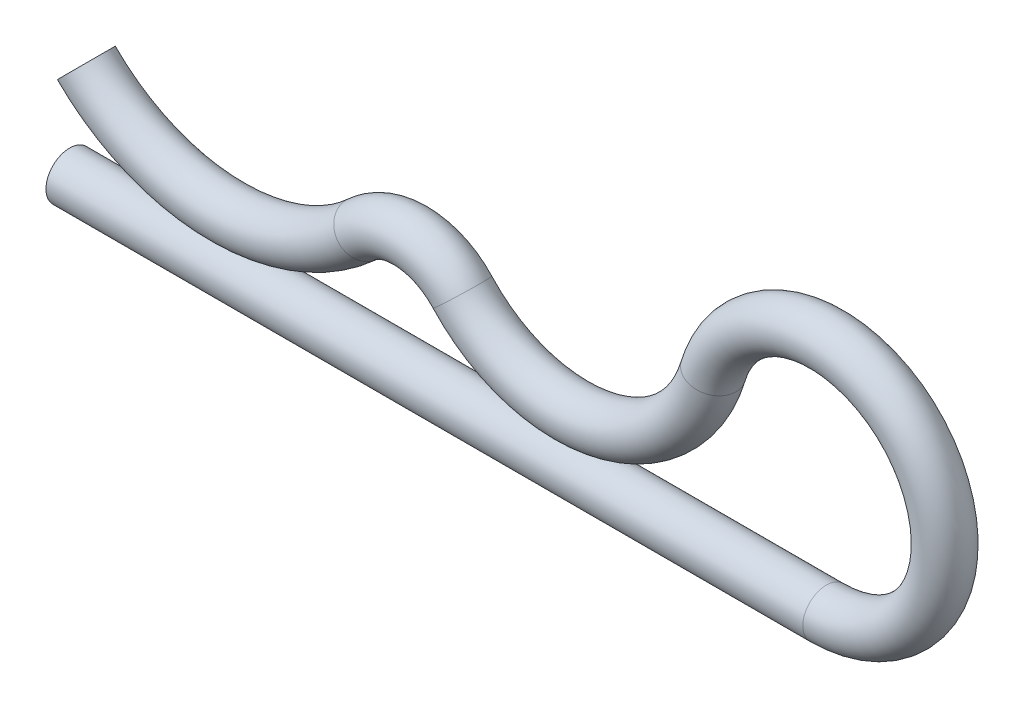
SolidWorks part; units mm, degrees
ref_plane "Front Plane" through (0, 0, 0) normal (0, 0, 1) x (1, 0, 0)
ref_plane "Top Plane" through (0, 0, 0) normal (0, 1, 0) x (1, 0, 0)
ref_plane "Right Plane" through (0, 0, 0) normal (1, 0, 0) x (0, 0, -1)
sketch "Sketch1" plane through (0, 0, 0) normal (0, 0, 1) x (1, 0, 0)
  line L0 (0, 0) -> (12.7, 0)
  line L1 (0, 0.7937) -> (12.7, 0.7937) construction
  line L2 (0.2806, 1.7751) -> (1.121, 0.9347) construction
  line L3 (0.2806, 1.7751) -> (0, 1.4944) construction
  arc A0 (12.7, 0) -> (10.8006, 2.5588) centre (12.7, 1.9844) ccw
  arc A1 (6.5924, 1.5986) -> (4.9113, 1.6722) centre (5.715, 0.7937) ccw
  arc A2 (6.5924, 1.5986) -> (10.8006, 2.5588) centre (8.4229, 3.2778) ccw
  arc A3 (0.2806, 1.7751) -> (4.9113, 1.6722) centre (2.6497, 4.1442) ccw
  dimension "D1" = 3.9688
  dimension "D3" = 2.3813
  dimension "D2" = 12.7
  dimension "D4" = 0.7937
  dimension "D5" = 5.715
  dimension "D6" = 0.7937
  dimension "D7" = 45
  dimension "D8" = 0.3969
sketch "Sketch2" plane through (0, 0, 0) normal (1, 0, 0) x (0, 0, -1)
  circle A0 centre (0, 0) radius 0.3969
  dimension "D1" = 0.7937
sweep "Sweep1" add profiles "Sketch2" path "Sketch1"
